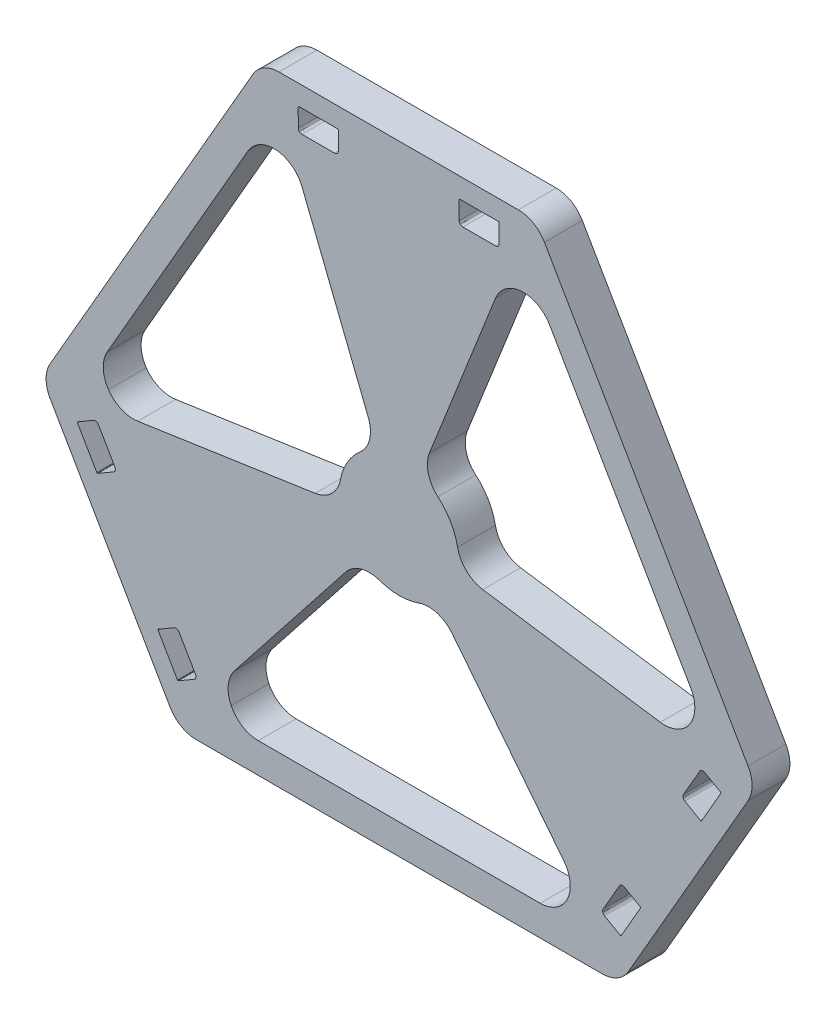
SolidWorks part; units mm, degrees
ref_plane "Alzado" through (0, 0, 0) normal (0, 0, 1) x (1, 0, 0)
ref_plane "Planta" through (0, 0, 0) normal (0, 1, 0) x (1, 0, 0)
ref_plane "Vista lateral" through (0, 0, 0) normal (1, 0, 0) x (0, 0, -1)
sketch "Model" plane through (0, 0, 0) normal (0, 0, 1) x (1, 0, 0)
  line L0 (122.3873, 59.4599) -> (77.6815, 59.4411)
  line L1 (77.6815, 59.4411) -> (122.3873, 59.4599)
  line L2 (73.9281, 67.1714) -> (91.5413, 89.531)
  line L3 (91.5413, 89.531) -> (73.9281, 67.1714)
  line L4 (108.4417, 89.5274) -> (126.1283, 67.2003)
  line L5 (126.1283, 67.2003) -> (108.4417, 89.5274)
  line L6 (86.716, 97.931) -> (58.5687, 93.7633)
  line L7 (58.5687, 93.7633) -> (86.716, 97.931)
  line L8 (53.7313, 100.8703) -> (76.0433, 139.6106)
  line L9 (76.0433, 139.6106) -> (53.7313, 100.8703)
  line L10 (84.6178, 138.9927) -> (95.1389, 112.5553)
  line L11 (95.1389, 112.5553) -> (84.6178, 138.9927)
  line L12 (104.8462, 112.5654) -> (115.3109, 139.0254)
  line L13 (115.3109, 139.0254) -> (104.8462, 112.5654)
  line L14 (123.8845, 139.6612) -> (146.2785, 100.9685)
  line L15 (146.2785, 100.9685) -> (123.8845, 139.6612)
  line L16 (141.4494, 93.8523) -> (113.2911, 98.003)
  line L17 (113.2911, 98.003) -> (141.4494, 93.8523)
  line L18 (61.8443, 66.8383) -> (64.3284, 68.276)
  line L19 (64.3284, 68.276) -> (61.8443, 66.8383)
  line L20 (65.1267, 68.0631) -> (67.7223, 63.5784)
  line L21 (67.7223, 63.5784) -> (65.1267, 68.0631)
  line L22 (67.5092, 62.7801) -> (65.0251, 61.3424)
  line L23 (65.0251, 61.3424) -> (67.5092, 62.7801)
  line L24 (64.8515, 61.3887) -> (61.7979, 66.6647)
  line L25 (61.7979, 66.6647) -> (64.8515, 61.3887)
  line L26 (49.0573, 88.9318) -> (51.5415, 90.3695)
  line L27 (51.5415, 90.3695) -> (49.0573, 88.9318)
  line L28 (52.3398, 90.1565) -> (54.9353, 85.6719)
  line L29 (54.9353, 85.6719) -> (52.3398, 90.1565)
  line L30 (54.7223, 84.8736) -> (52.2382, 83.4359)
  line L31 (52.2382, 83.4359) -> (54.7223, 84.8736)
  line L32 (52.0646, 83.4821) -> (49.011, 88.7582)
  line L33 (49.011, 88.7582) -> (52.0646, 83.4821)
  line L34 (115.9011, 149.6781) -> (115.9042, 146.8078)
  line L35 (115.9042, 146.8078) -> (115.9011, 149.6781)
  line L36 (115.3203, 146.2229) -> (110.1386, 146.2178)
  line L37 (110.1386, 146.2178) -> (115.3203, 146.2229)
  line L38 (109.554, 146.801) -> (109.551, 149.6712)
  line L39 (109.551, 149.6712) -> (109.554, 146.801)
  line L40 (109.6779, 149.7985) -> (115.7739, 149.8049)
  line L41 (115.7739, 149.8049) -> (109.6779, 149.7985)
  line L42 (90.374, 149.6509) -> (90.3771, 146.7807)
  line L43 (90.3771, 146.7807) -> (90.374, 149.6509)
  line L44 (89.7933, 146.1963) -> (84.612, 146.1905)
  line L45 (84.612, 146.1905) -> (89.7933, 146.1963)
  line L46 (84.0272, 146.7741) -> (84.0242, 149.6443)
  line L47 (84.0242, 149.6443) -> (84.0272, 146.7741)
  line L48 (84.1507, 149.7713) -> (90.2468, 149.7778)
  line L49 (90.2468, 149.7778) -> (84.1507, 149.7713)
  line L50 (147.8273, 83.5374) -> (145.3402, 84.9698)
  line L51 (145.3402, 84.9698) -> (147.8273, 83.5374)
  line L52 (145.1251, 85.7675) -> (147.7114, 90.2577)
  line L53 (147.7114, 90.2577) -> (145.1251, 85.7675)
  line L54 (148.5092, 90.4723) -> (150.9963, 89.0399)
  line L55 (150.9963, 89.0399) -> (148.5092, 90.4723)
  line L56 (151.0429, 88.8664) -> (148.0006, 83.5838)
  line L57 (148.0006, 83.5838) -> (151.0429, 88.8664)
  line L58 (135.0872, 61.4166) -> (132.6, 62.8491)
  line L59 (132.6, 62.8491) -> (135.0872, 61.4166)
  line L60 (132.3853, 63.6469) -> (134.9713, 68.137)
  line L61 (134.9713, 68.137) -> (132.3853, 63.6469)
  line L62 (135.7691, 68.3516) -> (138.2563, 66.9191)
  line L63 (138.2563, 66.9191) -> (135.7691, 68.3516)
  line L64 (138.3031, 66.746) -> (135.2607, 61.4634)
  line L65 (135.2607, 61.4634) -> (138.3031, 66.746)
  line L66 (155.3645, 94.8025) -> (123.0737, 150.595)
  line L67 (123.0737, 150.595) -> (155.3645, 94.8025)
  line L68 (118.9357, 152.9783) -> (80.9638, 152.9383)
  line L69 (80.9638, 152.9383) -> (118.9357, 152.9783)
  line L70 (76.8307, 150.5458) -> (44.6678, 94.701)
  line L71 (44.6678, 94.701) -> (76.8307, 150.5458)
  line L72 (44.6726, 89.9259) -> (63.703, 57.0449)
  line L73 (63.703, 57.0449) -> (44.6726, 89.9259)
  line L74 (67.838, 54.6618) -> (132.2587, 54.689)
  line L75 (132.2587, 54.689) -> (67.838, 54.6618)
  line L76 (136.3949, 57.0811) -> (155.3699, 90.0274)
  line L77 (155.3699, 90.0274) -> (136.3949, 57.0811)
  spline S0 degree 3 poles (126.1283, 67.2003) (127.268, 65.77) (127.489, 63.8141) (126.6975, 62.1653) knots 0 0 0 0 1 1 1 1
  spline S1 degree 3 poles (126.6975, 62.1653) (125.9063, 60.5167) (124.216, 59.4659) (122.3873, 59.4599) knots 0 0 0 0 1 1 1 1
  spline S2 degree 3 poles (77.6815, 59.4411) (75.8544, 59.4355) (74.1847, 60.4742) (73.3821, 62.1157) knots 0 0 0 0 1 1 1 1
  spline S3 degree 3 poles (73.3821, 62.1157) (72.5797, 63.757) (72.8014, 65.733) (73.9281, 67.1714) knots 0 0 0 0 1 1 1 1
  spline S4 degree 3 poles (91.5413, 89.531) (92.8038, 91.1351) (94.95, 91.7573) (96.876, 91.081) knots 0 0 0 0 1 1 1 1
  spline S5 degree 3 poles (96.876, 91.081) (98.8993, 90.3698) (101.1028, 90.3664) (103.1279, 91.0717) knots 0 0 0 0 1 1 1 1
  spline S6 degree 3 poles (103.1279, 91.0717) (105.0465, 91.7407) (107.1799, 91.1196) (108.4417, 89.5274) knots 0 0 0 0 1 1 1 1
  spline S7 degree 3 poles (95.1389, 112.5553) (95.8911, 110.6661) (95.3617, 108.506) (93.8236, 107.176) knots 0 0 0 0 1 1 1 1
  spline S8 degree 3 poles (93.8236, 107.176) (92.2038, 105.7767) (91.106, 103.8712) (90.7086, 101.7675) knots 0 0 0 0 1 1 1 1
  spline S9 degree 3 poles (90.7086, 101.7675) (90.3318, 99.7698) (88.7272, 98.2293) (86.716, 97.931) knots 0 0 0 0 1 1 1 1
  spline S10 degree 3 poles (58.5687, 93.7633) (56.7603, 93.4906) (54.9554, 94.2758) (53.9223, 95.7848) knots 0 0 0 0 1 1 1 1
  spline S11 degree 3 poles (53.9223, 95.7848) (52.8893, 97.2938) (52.8228, 99.2831) (53.7313, 100.8703) knots 0 0 0 0 1 1 1 1
  spline S12 degree 3 poles (76.0433, 139.6106) (76.9516, 141.1977) (78.6875, 142.1254) (80.5117, 141.9991) knots 0 0 0 0 1 1 1 1
  spline S13 degree 3 poles (80.5117, 141.9991) (82.3363, 141.8727) (83.937, 140.6901) (84.6178, 138.9927) knots 0 0 0 0 1 1 1 1
  spline S14 degree 3 poles (113.2911, 98.003) (111.2872, 98.2976) (109.6873, 99.8274) (109.3002, 101.8154) knots 0 0 0 0 1 1 1 1
  spline S15 degree 3 poles (109.3002, 101.8154) (108.8928, 103.9066) (107.7932, 105.7981) (106.1763, 107.1861) knots 0 0 0 0 1 1 1 1
  spline S16 degree 3 poles (106.1763, 107.1861) (104.6317, 108.5111) (104.0985, 110.6726) (104.8462, 112.5654) knots 0 0 0 0 1 1 1 1
  spline S17 degree 3 poles (115.3109, 139.0254) (115.9792, 140.7279) (117.5615, 141.8984) (119.3847, 142.0385) knots 0 0 0 0 1 1 1 1
  spline S18 degree 3 poles (119.3847, 142.0385) (121.2082, 142.1789) (122.9642, 141.2415) (123.8845, 139.6612) knots 0 0 0 0 1 1 1 1
  spline S19 degree 3 poles (146.2785, 100.9685) (147.1997, 99.3873) (147.1344, 97.4184) (146.111, 95.9013) knots 0 0 0 0 1 1 1 1
  spline S20 degree 3 poles (146.111, 95.9013) (145.0875, 94.3843) (143.2607, 93.5905) (141.4494, 93.8523) knots 0 0 0 0 1 1 1 1
  spline S21 degree 3 poles (61.7979, 66.6647) (61.7811, 66.6937) (61.7767, 66.7283) (61.7852, 66.7609) knots 0 0 0 0 1 1 1 1
  spline S22 degree 3 poles (61.7852, 66.7609) (61.7937, 66.7935) (61.8152, 66.8214) (61.8443, 66.8383) knots 0 0 0 0 1 1 1 1
  spline S23 degree 3 poles (64.3284, 68.276) (64.4624, 68.3536) (64.6218, 68.3749) (64.7714, 68.3351) knots 0 0 0 0 1 1 1 1
  spline S24 degree 3 poles (64.7714, 68.3351) (64.9211, 68.295) (65.049, 68.197) (65.1267, 68.0631) knots 0 0 0 0 1 1 1 1
  spline S25 degree 3 poles (67.7223, 63.5784) (67.7999, 63.4444) (67.8212, 63.2851) (67.7814, 63.1353) knots 0 0 0 0 1 1 1 1
  spline S26 degree 3 poles (67.7814, 63.1353) (67.7415, 62.9859) (67.6433, 62.8577) (67.5092, 62.7801) knots 0 0 0 0 1 1 1 1
  spline S27 degree 3 poles (65.0251, 61.3424) (64.996, 61.3255) (64.9615, 61.3207) (64.9289, 61.3295) knots 0 0 0 0 1 1 1 1
  spline S28 degree 3 poles (64.9289, 61.3295) (64.8962, 61.3383) (64.8686, 61.3594) (64.8515, 61.3887) knots 0 0 0 0 1 1 1 1
  spline S29 degree 3 poles (49.011, 88.7582) (48.9942, 88.7872) (48.9895, 88.822) (48.9983, 88.8544) knots 0 0 0 0 1 1 1 1
  spline S30 degree 3 poles (48.9983, 88.8544) (49.0068, 88.887) (49.0282, 88.9149) (49.0573, 88.9318) knots 0 0 0 0 1 1 1 1
  spline S31 degree 3 poles (51.5415, 90.3695) (51.6755, 90.4471) (51.8348, 90.4684) (51.9844, 90.4286) knots 0 0 0 0 1 1 1 1
  spline S32 degree 3 poles (51.9844, 90.4286) (52.134, 90.3888) (52.2623, 90.2902) (52.3398, 90.1565) knots 0 0 0 0 1 1 1 1
  spline S33 degree 3 poles (54.9353, 85.6719) (55.0129, 85.5379) (55.0343, 85.3786) (54.9945, 85.2288) knots 0 0 0 0 1 1 1 1
  spline S34 degree 3 poles (54.9945, 85.2288) (54.9545, 85.0793) (54.8563, 84.9512) (54.7223, 84.8736) knots 0 0 0 0 1 1 1 1
  spline S35 degree 3 poles (52.2382, 83.4359) (52.2091, 83.419) (52.1744, 83.4145) (52.1418, 83.4229) knots 0 0 0 0 1 1 1 1
  spline S36 degree 3 poles (52.1418, 83.4229) (52.1095, 83.4315) (52.0815, 83.4528) (52.0646, 83.4821) knots 0 0 0 0 1 1 1 1
  spline S37 degree 3 poles (115.7739, 149.8049) (115.8075, 149.8053) (115.8398, 149.7917) (115.8637, 149.7681) knots 0 0 0 0 1 1 1 1
  spline S38 degree 3 poles (115.8637, 149.7681) (115.8873, 149.7442) (115.9011, 149.7119) (115.9011, 149.6781) knots 0 0 0 0 1 1 1 1
  spline S39 degree 3 poles (115.9042, 146.8078) (115.9041, 146.6529) (115.8429, 146.5046) (115.7336, 146.3948) knots 0 0 0 0 1 1 1 1
  spline S40 degree 3 poles (115.7336, 146.3948) (115.6242, 146.2851) (115.4753, 146.2234) (115.3203, 146.2229) knots 0 0 0 0 1 1 1 1
  spline S41 degree 3 poles (110.1386, 146.2178) (109.9839, 146.2175) (109.8355, 146.2788) (109.7258, 146.3881) knots 0 0 0 0 1 1 1 1
  spline S42 degree 3 poles (109.7258, 146.3881) (109.616, 146.4974) (109.5543, 146.6463) (109.554, 146.801) knots 0 0 0 0 1 1 1 1
  spline S43 degree 3 poles (109.551, 149.6712) (109.5509, 149.705) (109.5642, 149.7372) (109.5881, 149.7612) knots 0 0 0 0 1 1 1 1
  spline S44 degree 3 poles (109.5881, 149.7612) (109.6118, 149.7851) (109.644, 149.7985) (109.6779, 149.7985) knots 0 0 0 0 1 1 1 1
  spline S45 degree 3 poles (90.2468, 149.7778) (90.2804, 149.7781) (90.313, 149.7648) (90.3366, 149.7409) knots 0 0 0 0 1 1 1 1
  spline S46 degree 3 poles (90.3366, 149.7409) (90.3605, 149.7173) (90.374, 149.6847) (90.374, 149.6509) knots 0 0 0 0 1 1 1 1
  spline S47 degree 3 poles (90.3771, 146.7807) (90.3773, 146.626) (90.3158, 146.4774) (90.2068, 146.3679) knots 0 0 0 0 1 1 1 1
  spline S48 degree 3 poles (90.2068, 146.3679) (90.0974, 146.2581) (89.9482, 146.1962) (89.7933, 146.1963) knots 0 0 0 0 1 1 1 1
  spline S49 degree 3 poles (84.612, 146.1905) (84.4572, 146.1902) (84.3084, 146.2516) (84.1986, 146.3609) knots 0 0 0 0 1 1 1 1
  spline S50 degree 3 poles (84.1986, 146.3609) (84.0891, 146.4699) (84.0272, 146.6192) (84.0272, 146.7741) knots 0 0 0 0 1 1 1 1
  spline S51 degree 3 poles (84.0242, 149.6443) (84.0238, 149.6779) (84.0374, 149.7102) (84.061, 149.7341) knots 0 0 0 0 1 1 1 1
  spline S52 degree 3 poles (84.061, 149.7341) (84.0847, 149.758) (84.1172, 149.7715) (84.1507, 149.7713) knots 0 0 0 0 1 1 1 1
  spline S53 degree 3 poles (148.0006, 83.5838) (147.984, 83.5548) (147.9564, 83.5334) (147.9236, 83.5246) knots 0 0 0 0 1 1 1 1
  spline S54 degree 3 poles (147.9236, 83.5246) (147.8911, 83.5159) (147.8563, 83.5204) (147.8273, 83.5374) knots 0 0 0 0 1 1 1 1
  spline S55 degree 3 poles (145.3402, 84.9698) (145.2058, 85.0469) (145.1077, 85.1742) (145.0676, 85.3239) knots 0 0 0 0 1 1 1 1
  spline S56 degree 3 poles (145.0676, 85.3239) (145.0272, 85.4733) (145.0482, 85.6334) (145.1251, 85.7675) knots 0 0 0 0 1 1 1 1
  spline S57 degree 3 poles (147.7114, 90.2577) (147.7886, 90.392) (147.9158, 90.4898) (148.0655, 90.5305) knots 0 0 0 0 1 1 1 1
  spline S58 degree 3 poles (148.0655, 90.5305) (148.2147, 90.5705) (148.3749, 90.5495) (148.5092, 90.4723) knots 0 0 0 0 1 1 1 1
  spline S59 degree 3 poles (150.9963, 89.0399) (151.0256, 89.0231) (151.0469, 88.9955) (151.0556, 88.9629) knots 0 0 0 0 1 1 1 1
  spline S60 degree 3 poles (151.0556, 88.9629) (151.0645, 88.9305) (151.0599, 88.8957) (151.0429, 88.8664) knots 0 0 0 0 1 1 1 1
  spline S61 degree 3 poles (135.2607, 61.4634) (135.2438, 61.4341) (135.2162, 61.4129) (135.1837, 61.4041) knots 0 0 0 0 1 1 1 1
  spline S62 degree 3 poles (135.1837, 61.4041) (135.1513, 61.3954) (135.1164, 61.3999) (135.0872, 61.4166) knots 0 0 0 0 1 1 1 1
  spline S63 degree 3 poles (132.6, 62.8491) (132.4657, 62.9263) (132.3679, 63.0537) (132.3274, 63.2032) knots 0 0 0 0 1 1 1 1
  spline S64 degree 3 poles (132.3274, 63.2032) (132.2869, 63.3527) (132.3081, 63.5127) (132.3853, 63.6469) knots 0 0 0 0 1 1 1 1
  spline S65 degree 3 poles (134.9713, 68.137) (135.0485, 68.2712) (135.1759, 68.3693) (135.3254, 68.4097) knots 0 0 0 0 1 1 1 1
  spline S66 degree 3 poles (135.3254, 68.4097) (135.4748, 68.4501) (135.635, 68.429) (135.7691, 68.3516) knots 0 0 0 0 1 1 1 1
  spline S67 degree 3 poles (138.2563, 66.9191) (138.2855, 66.9025) (138.3068, 66.8748) (138.3157, 66.8425) knots 0 0 0 0 1 1 1 1
  spline S68 degree 3 poles (138.3157, 66.8425) (138.3244, 66.8099) (138.3197, 66.775) (138.3031, 66.746) knots 0 0 0 0 1 1 1 1
  spline S69 degree 3 poles (155.3699, 90.0274) (156.221, 91.5063) (156.22, 93.3257) (155.3645, 94.8025) knots 0 0 0 0 1 1 1 1
  spline S70 degree 3 poles (123.0737, 150.595) (122.2185, 152.072) (120.6423, 152.9805) (118.9357, 152.9783) knots 0 0 0 0 1 1 1 1
  spline S71 degree 3 poles (80.9638, 152.9383) (79.2568, 152.936) (77.6821, 152.025) (76.8307, 150.5458) knots 0 0 0 0 1 1 1 1
  spline S72 degree 3 poles (44.6678, 94.701) (43.8164, 93.2219) (43.8176, 91.4026) (44.6726, 89.9259) knots 0 0 0 0 1 1 1 1
  spline S73 degree 3 poles (63.703, 57.0449) (64.5576, 55.5692) (66.1324, 54.6607) (67.838, 54.6618) knots 0 0 0 0 1 1 1 1
  spline S74 degree 3 poles (132.2587, 54.689) (133.9664, 54.69) (135.5428, 55.6011) (136.3949, 57.0811) knots 0 0 0 0 1 1 1 1
extrude "Saliente-Extruir1" add sketch "Model" along normal blind 6 contours L74 S74 L76 S69 L66 S70 L68 S71 L70 S72 L72 S73 S67 S68 L64 S61 S62 L58 S63 S64 L60 S65 S66 L62 S51 S52 L48 S45 S46 L42 S47 S48 L44 S49 S50 L46 S35 S36 L32 S29 S30 L26 S31 S32 L28 S33 S34 L30
